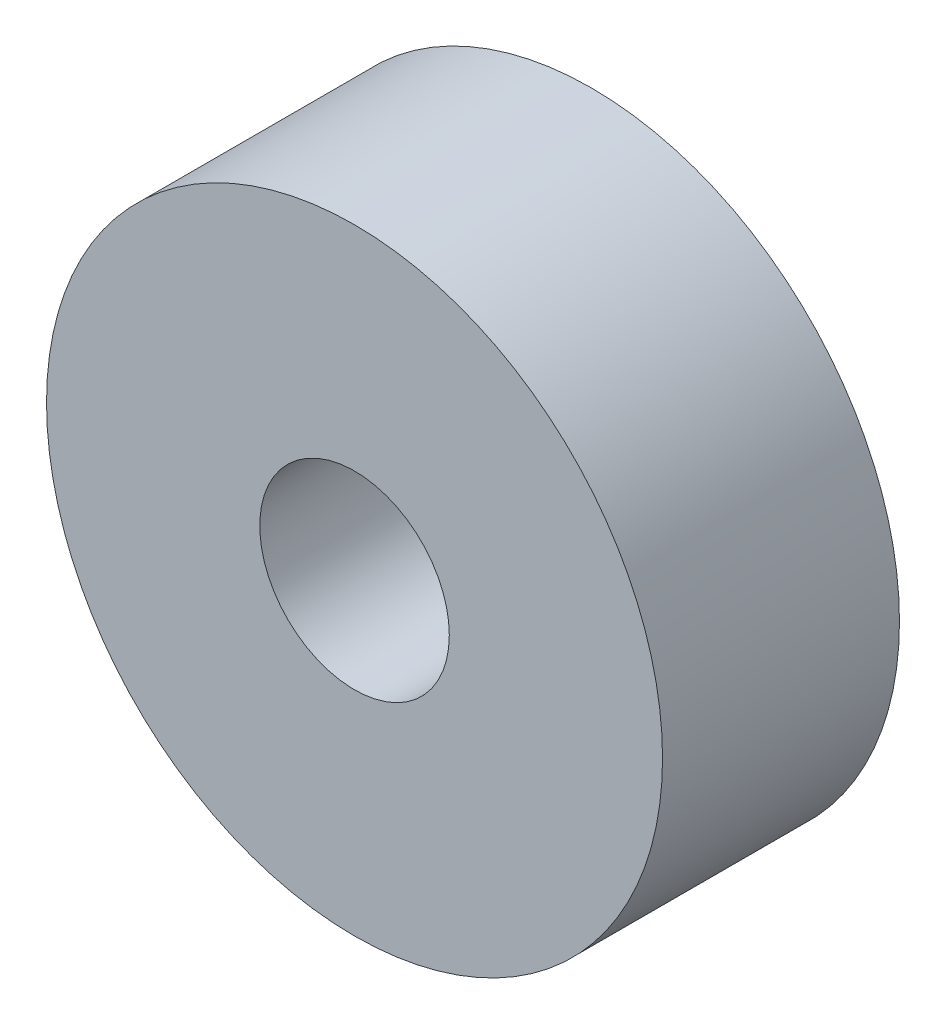
SolidWorks part; units mm, degrees
material "AISI 304"
ref_plane "Front" through (0, 0, 0) normal (0, 0, 1) x (1, 0, 0)
ref_plane "Top" through (0, 0, 0) normal (0, 1, 0) x (1, 0, 0)
ref_plane "Right" through (0, 0, 0) normal (1, 0, 0) x (0, 0, -1)
sketch "Sketch1" plane through (0, 0, 0) normal (0, 0, 1) x (1, 0, 0)
  circle A0 centre (0, 0) radius 6.5
  dimension "D1" = 13
extrude "Boss-Extrude1" add sketch "Sketch1" along normal blind 5
sketch "Sketch2" plane through (0, 0, 5) normal (0, 0, 1) x (1, 0, 0)
  circle A0 centre (0, 0) radius 2
  dimension "D1" = 4
extrude "Cut-Extrude1" cut sketch "Sketch2" against normal through all
